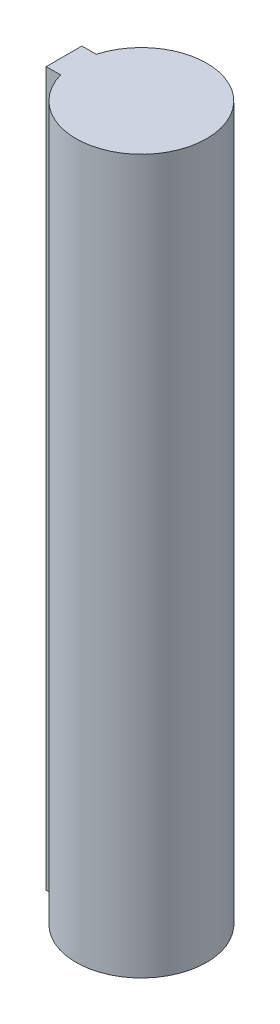
SolidWorks part; units mm, degrees
ref_plane "Front Plane" through (0, 0, 0) normal (0, 0, 1) x (1, 0, 0)
ref_plane "Top Plane" through (0, 0, 0) normal (0, 1, 0) x (1, 0, 0)
ref_plane "Right Plane" through (0, 0, 0) normal (1, 0, 0) x (0, 0, -1)
sketch "Sketch1" plane through (0, 0, 0) normal (0, 1, 0) x (1, 0, 0)
  line L1 (-6.5, 1.5) -> (-5.2915, 1.5)
  line L2 (-6.5, 1.5) -> (-6.5, -1.5)
  line L3 (-6.5, -1.5) -> (-5.2915, -1.5)
  arc A0 (-5.2915, -1.5) -> (-5.2915, 1.5) centre (0, 0) ccw
  point P3 (-5.5, 0)
  dimension "D1" = 11
  dimension "D3" = 3
extrude "Boss-Extrude1" add sketch "Sketch1" along normal blind 60
